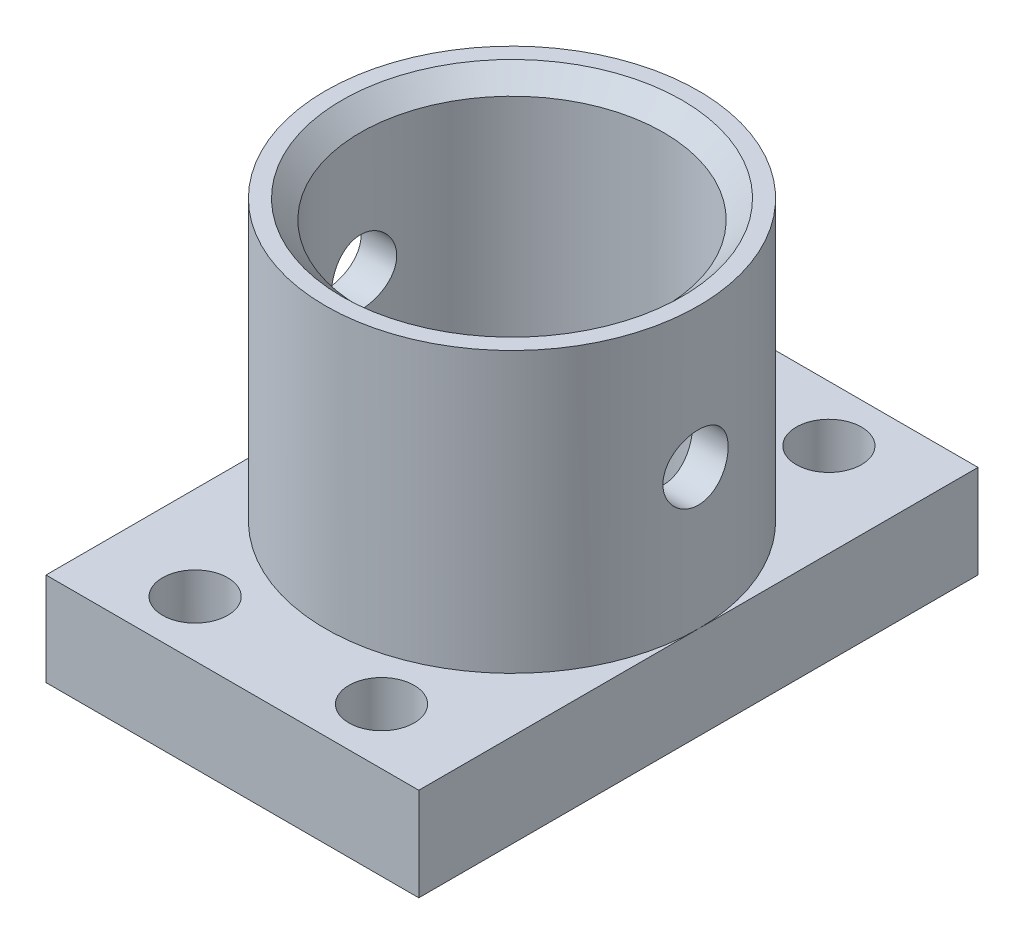
SolidWorks part; units mm, degrees
ref_plane "Front Plane" through (0, 0, 0) normal (0, 0, 1) x (1, 0, 0)
ref_plane "Top Plane" through (0, 0, 0) normal (0, 1, 0) x (1, 0, 0)
ref_plane "Right Plane" through (0, 0, 0) normal (1, 0, 0) x (0, 0, -1)
sketch "Sketch1" plane through (0, 0, 0) normal (0, 1, 0) x (1, 0, 0)
  line L1 (-10, -15) -> (10, -15)
  line L2 (-10, -15) -> (-10, 15)
  line L3 (-10, 15) -> (10, 15)
  line L4 (10, -15) -> (10, 15)
  line L5 (-10, -15) -> (10, 15) construction
  line L6 (-10, 15) -> (10, -15) construction
  point P0 (0, 0)
  dimension "D1" = 30
  dimension "D2" = 20
extrude "Boss-Extrude1" add sketch "Sketch1" along normal blind 5
sketch "Sketch2" plane through (0, 5, 0) normal (0, 1, 0) x (1, 0, 0)
  circle A0 centre (0, 0) radius 8.125
  circle A1 centre (0, 0) radius 10
  dimension "D1" = 16.25
  dimension "D2" = 20
extrude "Boss-Extrude2" add sketch "Sketch2" along normal blind 15
sketch "Sketch5" plane through (0, 5, 0) normal (0, 1, 0) x (1, 0, 0)
  circle A0 centre (0, 0) radius 8.125
  dimension "D1" = 16.25
extrude "Cut-Extrude3" cut sketch "Sketch5" against normal through all both and the other way through all
sketch "Sketch3" plane through (0, 5, 0) normal (0, 1, 0) x (1, 0, 0)
  line L0 (10, 15) -> (-10, 15) construction
  line L1 (-10, 15) -> (-10, 0) construction
  circle A0 centre (-5, 12) radius 1.75
  circle A1 centre (5, 12) radius 1.75
  circle A2 centre (5, -12) radius 1.75
  circle A3 centre (-5, -12) radius 1.75
  dimension "D1" = 3.5
  dimension "D2" = 3
  dimension "D3" = 5
  dimension "D4" = 2
  dimension "D5" = 2
extrude "Cut-Extrude1" cut sketch "Sketch3" against normal up to surface (5 mm away) up to face at (0, 0, 8.125)
chamfer "Chamfer1" distance 1 angle 45 1 edges at (0, 20, 8.125)
sketch "Sketch4" plane through (0, 0, 0) normal (1, 0, 0) x (0, 0, -1)
  circle A0 centre (0, 12.5) radius 1.75
  dimension "D2" = 3.5
  dimension "D1" = 12.5
extrude "Cut-Extrude2" cut sketch "Sketch4" against normal through all both and the other way through all
